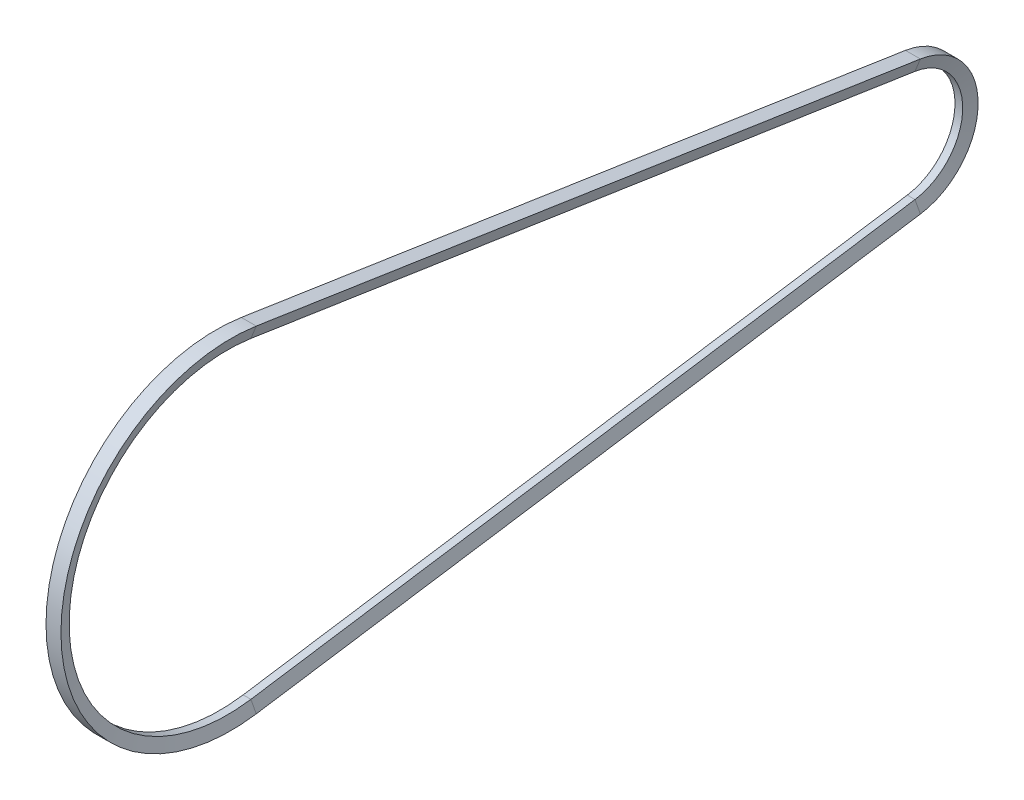
SolidWorks part; units mm, degrees
ref_plane "前视基准面" through (0, 0, 0) normal (0, 0, 1) x (1, 0, 0)
ref_plane "上视基准面" through (0, 0, 0) normal (0, 1, 0) x (1, 0, 0)
ref_plane "右视基准面" through (0, 0, 0) normal (1, 0, 0) x (0, 0, -1)
sketch "草图1" plane through (0, 0, 0) normal (1, 0, 0) x (0, 0, -1)
  line L0 (18.75, 123.5857) -> (507.5, 49.4343)
  line L1 (18.75, -123.5857) -> (507.5, -49.4343)
  line L2 (0, 0) -> (500, 0) construction
  arc A0 (18.75, 123.5857) -> (18.75, -123.5857) centre (0, 0) ccw
  arc A1 (507.5, -49.4343) -> (507.5, 49.4343) centre (500, 0) ccw
  dimension "D1" = 125
  dimension "D2" = 50
  dimension "D3" = 500
sketch "草图2" plane through (0, 0, 0) normal (0, 0, 1) x (1, 0, 0)
  line L0 (-5.5, 125) -> (5.5, 125)
  line L1 (5.5, 125) -> (2.8401, 116.3)
  line L2 (2.8401, 116.3) -> (-2.8401, 116.3)
  line L3 (-2.8401, 116.3) -> (-5.5, 125)
  line L4 (0, 116.3) -> (0, 125) construction
  line L5 (0, -125) -> (0, 125) construction
  dimension "D1" = 11
  dimension "D2" = 8.7
  dimension "D3" = 34
sweep "扫描1" add profiles "草图2" path "草图1"
equation "\"D3@草图1\" = \"D1@距离1@实心轮_椭圆辐轮.Assembly\""
equation "\"D1@草图2\" = \"bd@草图1@小带轮_实心轮.Part\" "
equation "\"D2@草图2\" = \"hf@草图1@小带轮_实心轮.Part\" "
equation "\"D3@草图2\" = \"槽轮角@草图1@小带轮_实心轮.Part\" "
equation "\"D2@草图1\" = \"dd@草图1@小带轮_实心轮.Part\"/2"
equation "\"D1@草图1\" = \"dd@草图1@大带轮_椭圆辐轮.Part\" /2"
